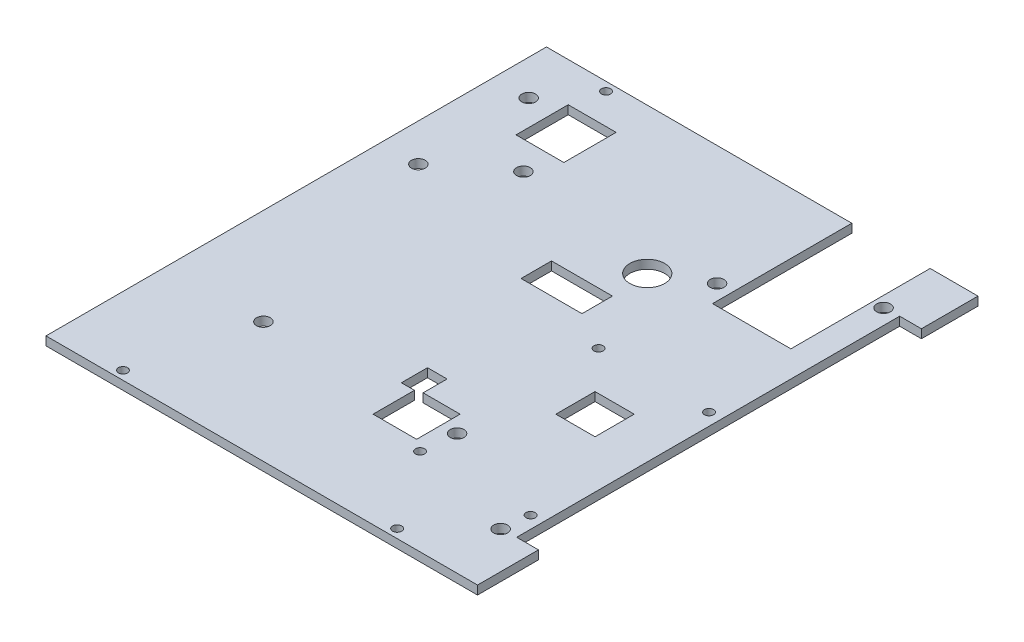
SolidWorks part; units mm, degrees
ref_plane "前视基准面" through (0, 0, 0) normal (0, 0, 1) x (1, 0, 0)
ref_plane "上视基准面" through (0, 0, 0) normal (0, 1, 0) x (1, 0, 0)
ref_plane "右视基准面" through (0, 0, 0) normal (1, 0, 0) x (0, 0, -1)
sketch "草图1" plane through (0, 0, 0) normal (0, 1, 0) x (1, 0, 0)
  line L0 (4.52, -15.78) -> (12.69, -15.78) construction
  line L1 (0, 0) -> (99.16, 0)
  line L2 (0, 0) -> (0, -115)
  line L3 (0, -115) -> (99.16, -115)
  line L4 (99.16, 0) -> (99.16, -115)
  line L5 (17.74, -23.04) -> (71.08, -23.04) construction
  line L6 (17.74, -23.04) -> (17.74, -91.62) construction
  line L7 (17.74, -91.62) -> (71.08, -91.62) construction
  line L8 (71.08, -23.04) -> (71.08, -91.62) construction
  line L9 (22.16, -27.46) -> (66.66, -27.46) construction
  line L10 (22.16, -27.46) -> (22.16, -87.2) construction
  line L11 (22.16, -87.2) -> (66.66, -87.2) construction
  line L12 (66.66, -27.46) -> (66.66, -87.2) construction
  line L13 (99.16, -8.9) -> (-0.14, -8.9) construction
  line L14 (99.16, -8.9) -> (99.16, -105.5) construction
  line L15 (99.16, -105.5) -> (-0.14, -105.5) construction
  line L16 (-0.14, -8.9) -> (-0.14, -105.5) construction
  line L17 (4.52, -8.9) -> (12.69, -8.9) construction
  line L18 (4.52, -8.9) -> (4.52, -42.03) construction
  line L19 (4.52, -42.03) -> (12.69, -42.03) construction
  line L20 (12.69, -8.9) -> (12.69, -42.03) construction
  line L21 (4.52, -34.06) -> (12.69, -34.06) construction
  line L23 (13.69, 0) -> (80.69, 0) construction
  line L24 (13.69, 0) -> (13.69, -115) construction
  line L25 (13.69, -115) -> (80.69, -115) construction
  line L26 (80.69, 0) -> (80.69, -115) construction
  line L27 (15.69, -2) -> (78.69, -2) construction
  line L28 (15.69, -2) -> (15.69, -113) construction
  line L29 (15.69, -113) -> (78.69, -113) construction
  line L30 (78.69, -2) -> (78.69, -113) construction
  line L31 (4.52, -8.9) -> (12.69, -8.9)
  line L32 (4.52, -8.9) -> (4.52, -15.78)
  line L33 (4.52, -15.78) -> (12.69, -15.78)
  line L34 (12.69, -8.9) -> (12.69, -15.78)
  line L35 (4.52, -34.06) -> (12.69, -34.06)
  line L36 (4.52, -34.06) -> (4.52, -42.03)
  line L37 (4.52, -42.03) -> (12.69, -42.03)
  line L38 (12.69, -34.06) -> (12.69, -42.03)
  line L47 (99.16, -13) -> (94.16, -13)
  line L48 (99.16, -13) -> (99.16, -101)
  line L49 (99.16, -101) -> (94.16, -101)
  line L50 (94.16, -13) -> (94.16, -101)
  line L51 (43.16, -42) -> (57.16, -42)
  line L52 (43.16, -42) -> (43.16, -49)
  line L53 (43.16, -49) -> (57.16, -49)
  line L54 (57.16, -42) -> (57.16, -49)
  line L55 (50.16, -77.5) -> (54.66, -77.5)
  line L56 (50.16, -77.5) -> (50.16, -83.5)
  line L57 (50.16, -83.5) -> (54.66, -83.5)
  line L58 (54.66, -77.5) -> (54.66, -83.5)
  line L59 (53.16, -93) -> (63.16, -93)
  line L60 (53.16, -93) -> (53.16, -83)
  line L61 (53.16, -83) -> (63.16, -83)
  line L62 (63.16, -93) -> (63.16, -83)
  line L63 (70.16, 0) -> (88.16, 0)
  line L64 (70.16, 0) -> (70.16, -32)
  line L65 (70.16, -32) -> (88.16, -32)
  line L66 (88.16, 0) -> (88.16, -32)
  line L67 (63.96, -52) -> (93.36, -52) construction
  line L68 (63.96, -52) -> (63.96, -97) construction
  line L69 (63.96, -97) -> (93.36, -97) construction
  line L70 (93.36, -52) -> (93.36, -97) construction
  line L71 (65.96, -54) -> (91.36, -54) construction
  line L72 (65.96, -54) -> (65.96, -95) construction
  line L73 (65.96, -95) -> (91.36, -95) construction
  line L74 (91.36, -54) -> (91.36, -95) construction
  line L75 (74.16, -63) -> (83.16, -63)
  line L76 (74.16, -63) -> (74.16, -72)
  line L77 (74.16, -72) -> (83.16, -72)
  line L78 (83.16, -63) -> (83.16, -72)
  line L79 (14, -9) -> (25, -9)
  line L80 (14, -9) -> (14, -21)
  line L81 (14, -21) -> (25, -21)
  line L82 (25, -9) -> (25, -21)
  circle A0 centre (22.16, -27.46) radius 1.585
  circle A1 centre (66.66, -27.46) radius 1.585
  circle A2 centre (22.16, -87.2) radius 1.585
  circle A3 centre (66.66, -87.2) radius 1.585
  circle A4 centre (90.66, -13.2) radius 1.585
  circle A5 centre (90.66, -101.2) radius 1.585
  circle A6 centre (8.12, -12.2) radius 1.585
  circle A7 centre (8.62, -38.06) radius 1.585
  circle A8 centre (15.69, -2) radius 1.05
  circle A9 centre (78.69, -2) radius 1.05
  circle A10 centre (15.69, -113) radius 1.05
  circle A11 centre (78.69, -113) radius 1.05
  circle A12 centre (56.66, -33.5) radius 4
  circle A13 centre (65.96, -54) radius 1.05
  circle A14 centre (91.36, -54) radius 1.05
  circle A15 centre (65.96, -95) radius 1.05
  circle A16 centre (91.36, -95) radius 1.05
  dimension "D11" = 3.17
  dimension "D12" = 3.17
  dimension "D13" = 3.17
  dimension "D14" = 3.17
  dimension "D19" = 3.17
  dimension "D22" = 3.17
  dimension "D30" = 3.17
  dimension "D33" = 3.17
  dimension "D42" = 2.1
  dimension "D43" = 2.1
  dimension "D44" = 2.1
  dimension "D45" = 2.1
  dimension "D55" = 8
  dimension "D74" = 2.1
  dimension "D75" = 2.1
  dimension "D76" = 2.1
  dimension "D77" = 2.1
  dimension "D2" = 115
  dimension "D3" = 53.34
  dimension "D4" = 68.58
  dimension "D5" = 4.42
  dimension "D6" = 4.42
  dimension "D7" = 4.42
  dimension "D8" = 4.42
  dimension "D9" = 99.3
  dimension "D10" = 96.6
  dimension "D15" = 68.5
  dimension "D16" = 74
  dimension "D17" = 18.3
  dimension "D18" = 22.3
  dimension "D20" = 68.5
  dimension "D21" = 14
  dimension "D23" = 94.64
  dimension "D24" = 8.17
  dimension "D25" = 6.88
  dimension "D26" = 18.28
  dimension "D27" = 7.97
  dimension "D28" = 3.6
  dimension "D29" = 3.3
  dimension "D31" = 4.1
  dimension "D32" = 4
  dimension "D34" = 9.5
  dimension "D35" = 2
  dimension "D36" = 2
  dimension "D37" = 2
  dimension "D38" = 2
  dimension "D39" = 67
  dimension "D40" = 115
  dimension "D41" = 1
  dimension "D46" = 99.16
  dimension "D47" = 13
  dimension "D48" = 5
  dimension "D49" = 88
  dimension "D50" = 11
  dimension "D51" = 18
  dimension "D52" = 32
  dimension "D53" = 33.5
  dimension "D54" = 42.5
  dimension "D56" = 42
  dimension "D57" = 7
  dimension "D58" = 42
  dimension "D59" = 14
  dimension "D60" = 77.5
  dimension "D61" = 6
  dimension "D62" = 44.5
  dimension "D63" = 4.5
  dimension "D64" = 83
  dimension "D65" = 10
  dimension "D66" = 36
  dimension "D67" = 10
  dimension "D68" = 2
  dimension "D69" = 2
  dimension "D70" = 2
  dimension "D71" = 2
  dimension "D72" = 45
  dimension "D73" = 29.4
  dimension "D78" = 18
  dimension "D79" = 2.7
  dimension "D80" = 43
  dimension "D81" = 9
  dimension "D82" = 16
  dimension "D83" = 9
  dimension "D84" = 14
  dimension "D85" = 11
  dimension "D86" = 9
  dimension "D87" = 12
extrude "凸台-拉伸1" add sketch "草图1" along normal blind 2 contours L4 L1 L2 L3 A11 A10 A9 A8 A5 A4 A3 A2 A1 A0 | L32 L33 L2 L31 A6 | L36 L37 L2 L35 A7
